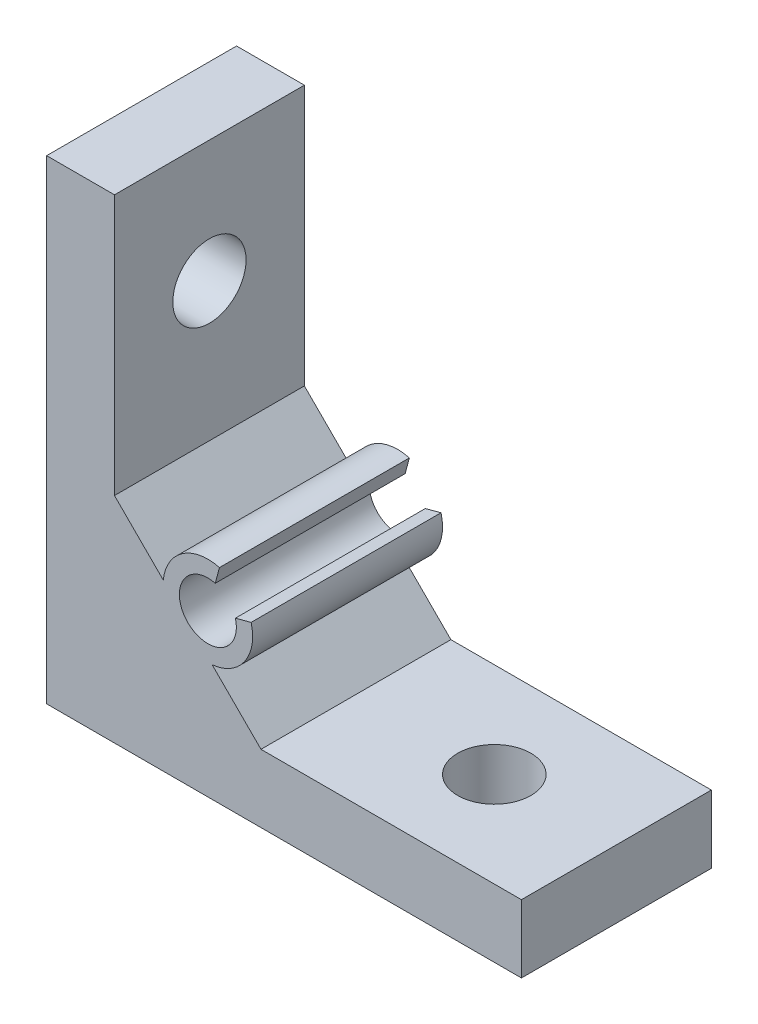
SolidWorks part; units mm, degrees
ref_plane "Front Plane" through (0, 0, 0) normal (0, 0, 1) x (1, 0, 0)
ref_plane "Top Plane" through (0, 0, 0) normal (0, 1, 0) x (1, 0, 0)
ref_plane "Right Plane" through (0, 0, 0) normal (1, 0, 0) x (0, 0, -1)
sketch "Sketch1" plane through (0, 0, 0) normal (0, 0, 1) x (1, 0, 0)
  line L0 (0, 35) -> (0, 0)
  line L1 (0, 0) -> (35, 0)
  line L2 (35, 0) -> (35, 5)
  line L3 (35, 5) -> (15.8, 5)
  line L4 (15.8, 5) -> (12.2, 8.6)
  line L5 (5, 15.8) -> (5, 35)
  line L6 (5, 35) -> (0, 35)
  line L7 (12.739, 15.0725) -> (12.4284, 13.9134)
  line L8 (13.9134, 12.4284) -> (15.0725, 12.739)
  line L9 (8.6, 12.2) -> (5, 15.8)
  arc A0 (12.4284, 13.9134) -> (13.9134, 12.4284) centre (11.8849, 11.8849) ccw
  arc A1 (12.739, 15.0725) -> (8.6, 12.2) centre (11.8849, 11.8849) ccw
  arc A2 (12.2, 8.6) -> (15.0725, 12.739) centre (11.8849, 11.8849) ccw
  dimension "D4" = 4.2
  dimension "D5" = 6.6
  dimension "D1" = 35
  dimension "D2" = 5
  dimension "D3" = 19.2
  dimension "D6" = 15
  dimension "D7" = 15
extrude "Boss-Extrude1" add sketch "Sketch1" along normal mid plane 14
sketch "Sketch3" plane through (0, 5, 0) normal (0, 1, 0) x (1, 0, 0)
  line L0 (35, 0) -> (26, 0) construction
  line L1 (35, -7) -> (35, 7) construction
  circle A0 centre (26, 0) radius 2.7
  dimension "D1" = 5.4
  dimension "D2" = 9
extrude "Cut-Extrude1" cut sketch "Sketch3" against normal through all
sketch "Sketch4" plane through (5, 0, 0) normal (1, 0, 0) x (0, 0, -1)
  line L0 (0, 35) -> (0, 26) construction
  line L1 (-7, 35) -> (7, 35) construction
  circle A0 centre (0, 26) radius 2.7
  dimension "D2" = 5.4
  dimension "D1" = 9
extrude "Cut-Extrude2" cut sketch "Sketch4" against normal through all
